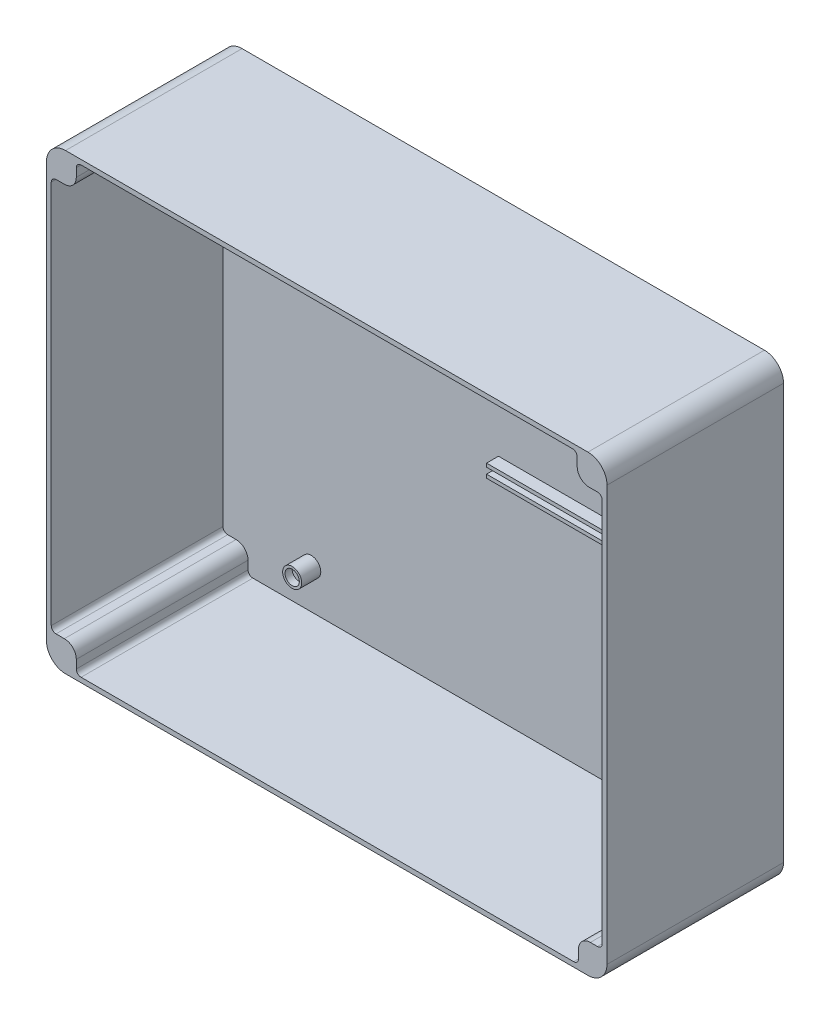
SolidWorks part; units mm, degrees
ref_plane "Front Plane" through (0, 0, 0) normal (0, 0, 1) x (1, 0, 0)
ref_plane "Top Plane" through (0, 0, 0) normal (0, 1, 0) x (1, 0, 0)
ref_plane "Right Plane" through (0, 0, 0) normal (1, 0, 0) x (0, 0, -1)
sketch "Sketch1" plane through (0, 0, 0) normal (0, 0, 1) x (1, 0, 0)
  line L1 (-117.5, 95) -> (117.5, 95)
  line L2 (-117.5, 95) -> (-117.5, -95)
  line L3 (-117.5, -95) -> (117.5, -95)
  line L4 (117.5, 95) -> (117.5, -95)
  line L5 (-117.5, 95) -> (117.5, -95) construction
  line L6 (-117.5, -95) -> (117.5, 95) construction
  point P0 (0, 0)
  dimension "D1" = 235
  dimension "D2" = 190
extrude "Boss-Extrude1" add sketch "Sketch1" along normal blind 74
sketch "Sketch2" plane through (0, 0, 74) normal (0, 0, 1) x (1, 0, 0)
  line L5 (-117.5, 95) -> (-105, 95)
  line L6 (-117.5, 95) -> (-117.5, 82.5)
  line L7 (-117.5, 82.5) -> (-105, 82.5)
  line L8 (115.5, -93) -> (115.5, 93)
  line L9 (115.5, 93) -> (-115.5, 93)
  line L10 (-115.5, 93) -> (-115.5, -93)
  line L11 (-115.5, -93) -> (115.5, -93)
  line L12 (115.5, -82.5) -> (115.5, 82.5)
  line L13 (105, 93) -> (-105, 93)
  line L14 (-115.5, 82.5) -> (-115.5, -82.5)
  line L15 (-105, -93) -> (105.5348, -93)
  line L16 (-105, 95) -> (-105, 82.5)
  line L17 (117.5, 95) -> (105, 95)
  line L18 (117.5, 95) -> (117.5, 82.5)
  line L19 (117.5, 82.5) -> (105, 82.5)
  line L20 (105, 95) -> (105, 82.5)
  line L21 (117.5, -95) -> (105.5348, -95)
  line L22 (117.5, -95) -> (117.5, -82.5)
  line L23 (117.5, -82.5) -> (105.5348, -82.5)
  line L24 (105.5348, -95) -> (105.5348, -82.5)
  line L25 (-117.5, -95) -> (-105, -95)
  line L26 (-117.5, -95) -> (-117.5, -82.5)
  line L27 (-117.5, -82.5) -> (-105, -82.5)
  line L28 (-105, -95) -> (-105, -82.5)
  dimension "D2" = 12.5
  dimension "D3" = 12.5
  dimension "D4" = 12.5
  dimension "D5" = 12.5
  dimension "D6" = 12.5
  dimension "D7" = 12.5
  dimension "D8" = 12.5
  dimension "D9" = 11.9652
  dimension "D1" = 2
extrude "Cut-Extrude1" cut sketch "Sketch2" against normal blind 72 contours L28 L15 L24 L23 L12 L19 L20 L13 L16 L7 L14 L27
fillet "Fillet1" radius 2 8 edges at (-105, -93, 38) (-115.5, -82.5, 38) (105.5348, -93, 38) (115.5, -82.5, 38) (115.5, 82.5, 38) (105, 93, 38) (-105, 93, 38) (-115.5, 82.5, 38)
fillet "Fillet2" radius 5 4 edges at (-105, -82.5, 38) (105.5348, -82.5, 38) (105, 82.5, 38) (-105, 82.5, 38)
sketch "Sketch3" plane through (0, 0, 2) normal (0, 0, 1) x (1, 0, 0)
  line L1 (-78.5, 76.505) -> (78.5, 76.505) construction
  line L2 (-78.5, 76.505) -> (-78.5, -76.505) construction
  line L3 (-78.5, -76.505) -> (78.5, -76.505) construction
  line L4 (78.5, 76.505) -> (78.5, -76.505) construction
  line L5 (-78.5, 76.505) -> (78.5, -76.505) construction
  line L6 (-78.5, -76.505) -> (78.5, 76.505) construction
  circle A0 centre (-78.5, 76.505) radius 4
  circle A1 centre (78.5, 76.505) radius 4
  circle A2 centre (78.5, -76.505) radius 4
  circle A3 centre (-78.5, -76.505) radius 4
  point P0 (0, 0)
  dimension "D3" = 8
  dimension "D1" = 157
  dimension "D2" = 153.01
extrude "Boss-Extrude2" add sketch "Sketch3" along normal blind 8
fillet "Fillet3" radius 8 4 edges at (117.5, -95, 37) (-117.5, -95, 37) (-117.5, 95, 37) (117.5, 95, 37)
sketch "Sketch4" plane through (0, 0, 10) normal (0, 0, 1) x (1, 0, 0)
  circle A5 centre (78.5, 76.505) radius 3
  circle A6 centre (78.5, 76.505) radius 3
  circle A8 centre (78.5, -76.505) radius 3
  circle A9 centre (78.5, -76.505) radius 3
  circle A11 centre (-78.5, -76.505) radius 3
  circle A12 centre (-78.5, -76.505) radius 3
  circle A13 centre (-78.5, 76.505) radius 3
  circle A14 centre (-78.5, 76.505) radius 3
  dimension "D1" = 1
  dimension "D2" = 1
  dimension "D3" = 1
  dimension "D4" = 1
extrude "Cut-Extrude2" cut sketch "Sketch4" against normal blind 3
sketch "Sketch5" plane through (0, 0, 2) normal (0, 0, 1) x (1, 0, 0)
  line L0 (0, 108.4368) -> (0, -128.0619) construction
  line L1 (-146.8554, 0) -> (177.7899, 0) construction
  line L2 (113.5, 82.5) -> (110, 82.5) construction
  line L3 (110.5, 82.5) -> (109.5, 82.5)
  line L4 (110.5, 82.5) -> (110.5, -82.5)
  line L5 (110.5, -82.5) -> (109.5, -82.5)
  line L6 (109.5, 82.5) -> (109.5, -82.5)
  line L7 (113.5, -82.5) -> (110.5348, -82.5) construction
  line L8 (115.5, -80.5) -> (115.5, 80.5) construction
  dimension "D1" = 1
  dimension "D2" = 5
extrude "Boss-Extrude3" add sketch "Sketch5" along normal blind 5
sketch "Sketch6" plane through (0, 0, 2) normal (0, 0, 1) x (1, 0, 0)
  line L0 (0, 0) -> (141.5541, 0) construction
  line L1 (115.5, -80.5) -> (115.5, 80.5) construction
  line L2 (0, 2.75) -> (115.5, 2.75)
  line L3 (0, 2.75) -> (0, 1.25)
  line L4 (0, 1.25) -> (115.5, 1.25)
  line L5 (115.5, 2.75) -> (115.5, 1.25)
  line L6 (0, -1.25) -> (115.5, -1.25)
  line L7 (115.5, -2.75) -> (115.5, -1.25)
  line L8 (0, -2.75) -> (115.5, -2.75)
  line L9 (0, -2.75) -> (0, -1.25)
  dimension "D1" = 1.5
  dimension "D2" = 2.5
extrude "Boss-Extrude4" add sketch "Sketch6" along normal up to surface (5 mm away) up to face at (110, 16.5, 7)
sketch "Sketch7" plane through (0, -2.75, 0) normal (0, -1, 0) x (1, 0, 0)
  line L0 (107.5, 7) -> (115.5, 64)
  line L1 (109.5, 7) -> (0, 7) construction
  line L2 (115.5, 74) -> (115.5, 2) construction
  line L3 (115.5, 64) -> (115.5, 7)
  line L4 (107.5, 7) -> (115.5, 7)
  dimension "D1" = 8
  dimension "D2" = 57
extrude "Boss-Extrude5" add sketch "Sketch7" against normal blind 1.5
mirror "Mirror1" about plane through (0, 0, 0) normal (0, 1, 0) of "Boss-Extrude5"
sketch "Sketch8" plane through (109.5, 0, 0) normal (-1, 0, 0) x (0, 0, 1)
  line L4 (2, -1.25) -> (7, -1.25)
  line L5 (7, -1.25) -> (7, 1.25)
  line L6 (7, 1.25) -> (2, 1.25)
  line L7 (2, 1.25) -> (2, -1.25)
  line L8 (2, -1.25) -> (7, -1.25)
  line L9 (7, -1.25) -> (7, 1.25)
  line L10 (7, 1.25) -> (2, 1.25)
  line L11 (2, 1.25) -> (2, -1.25)
  dimension "D1" = 0
extrude "Cut-Extrude3" cut sketch "Sketch8" against normal blind 5
equation "\"D3@Sketch2\"=\"D2@Sketch2\""
equation "\"D4@Sketch2\"=\"D2@Sketch2\""
equation "\"D5@Sketch2\"=\"D2@Sketch2\""
equation "\"D6@Sketch2\"=\"D2@Sketch2\""
equation "\"D7@Sketch2\"=\"D2@Sketch2\""
equation "\"D8@Sketch2\"=\"D2@Sketch2\""
